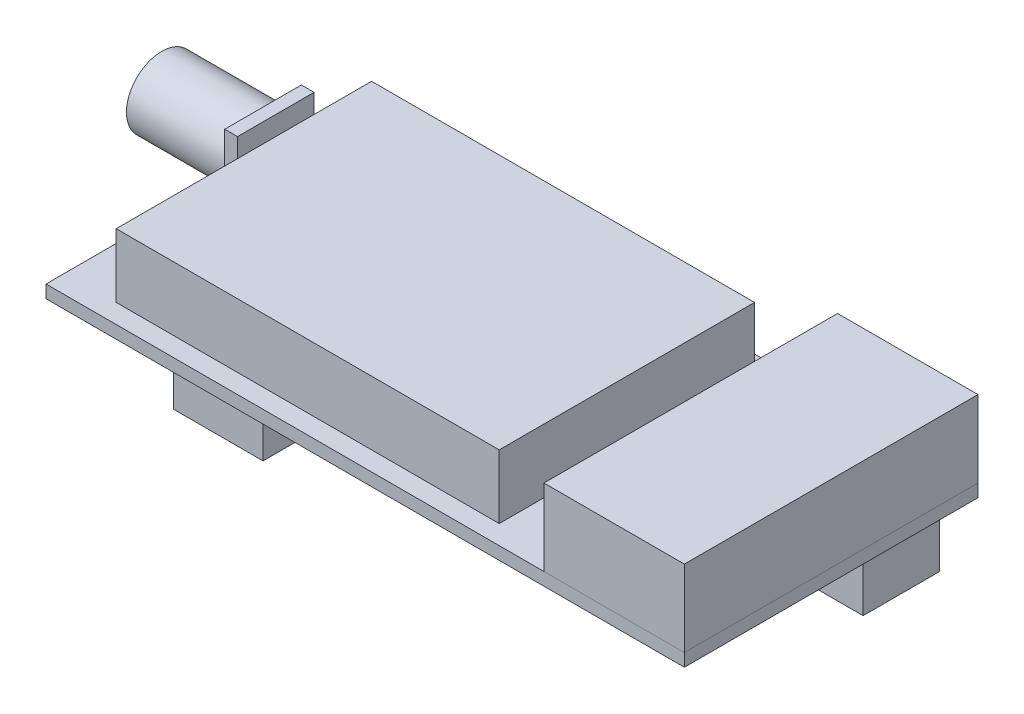
SolidWorks part; units mm, degrees
ref_plane "Front Plane" through (0, 0, 0) normal (0, 0, 1) x (1, 0, 0)
ref_plane "Top Plane" through (0, 0, 0) normal (0, 1, 0) x (1, 0, 0)
ref_plane "Right Plane" through (0, 0, 0) normal (1, 0, 0) x (0, 0, -1)
sketch "Sketch1" plane through (0, 0, 0) normal (0, 1, 0) x (1, 0, 0)
  line L1 (25, 11.5) -> (-25, 11.5)
  line L2 (25, 11.5) -> (25, -11.5)
  line L3 (25, -11.5) -> (-25, -11.5)
  line L4 (-25, 11.5) -> (-25, -11.5)
  line L5 (25, 11.5) -> (-25, -11.5) construction
  line L6 (25, -11.5) -> (-25, 11.5) construction
  point P0 (0, 0)
  dimension "D1" = 50
  dimension "D2" = 23
extrude "Boss-Extrude1" add sketch "Sketch1" along normal mid plane 1
sketch "Sketch2" plane through (0, 0.5, 0) normal (0, 1, 0) x (1, 0, 0)
  line L0 (0, 0) -> (-50000, 0) construction
  line L1 (-21, 10) -> (9, 10)
  line L2 (-21, 10) -> (-21, -10)
  line L3 (-21, -10) -> (9, -10)
  line L4 (9, 10) -> (9, -10)
  line L5 (-25, 11.5) -> (-25, -11.5) construction
  dimension "D1" = 30
  dimension "D2" = 20
  dimension "D3" = 4
extrude "Boss-Extrude2" add sketch "Sketch2" along normal blind 5 separate body
sketch "Sketch3" plane through (0, -0.5, 0) normal (0, -1, 0) x (1, 0, 0)
  line L0 (-25, -11.5) -> (-25, 11.5) construction
  line L1 (-17, 9.5) -> (-10, 9.5)
  line L2 (-17, 9.5) -> (-17, 2.5)
  line L3 (-17, 2.5) -> (-10, 2.5)
  line L4 (-10, 9.5) -> (-10, 2.5)
  line L5 (-25, 11.5) -> (25, 11.5) construction
  line L6 (25, 11.5) -> (25, -11.5) construction
  line L7 (20, -3.5) -> (24, -3.5)
  line L8 (20, -3.5) -> (20, -9.5)
  line L9 (20, -9.5) -> (24, -9.5)
  line L10 (24, -3.5) -> (24, -9.5)
  line L11 (25, -11.5) -> (-25, -11.5) construction
  dimension "D1" = 7
  dimension "D2" = 7
  dimension "D3" = 8
  dimension "D4" = 2
  dimension "D5" = 6
  dimension "D6" = 4
  dimension "D7" = 1
  dimension "D8" = 2
extrude "Boss-Extrude3" add sketch "Sketch3" along normal blind 4.5 separate body
sketch "Sketch4" plane through (-25, 0, 0) normal (-1, 0, 0) x (0, 0, 1)
  line L0 (0, 0) -> (-50000, 0) construction
  line L1 (-9.5, 3) -> (-3.5, 3)
  line L2 (-9.5, 3) -> (-9.5, -3)
  line L3 (-9.5, -3) -> (-3.5, -3)
  line L4 (-3.5, 3) -> (-3.5, -3)
  line L6 (-11.5, 0.5) -> (-11.5, -0.5) construction
  dimension "D1" = 6
  dimension "D2" = 6
  dimension "D3" = 2
extrude "Boss-Extrude4" add sketch "Sketch4" along normal blind 1 separate body
sketch "Sketch5" plane through (-26, 0, 0) normal (-1, 0, 0) x (0, 0, 1)
  circle A0 centre (-6.5528, 0) radius 2.75
  dimension "D1" = 5.5
extrude "Boss-Extrude5" add sketch "Sketch5" along normal blind 8
sketch "Sketch6" plane through (0, 0.5, 0) normal (0, 1, 0) x (1, 0, 0)
  line L0 (25, 11.5) -> (-25, 11.5) construction
  line L1 (14, 11.5) -> (25, 11.5)
  line L2 (14, 11.5) -> (14, -11.5)
  line L3 (14, -11.5) -> (25, -11.5)
  line L4 (25, 11.5) -> (25, -11.5)
  dimension "D1" = 11
extrude "Boss-Extrude6" add sketch "Sketch6" along normal blind 6 separate body
